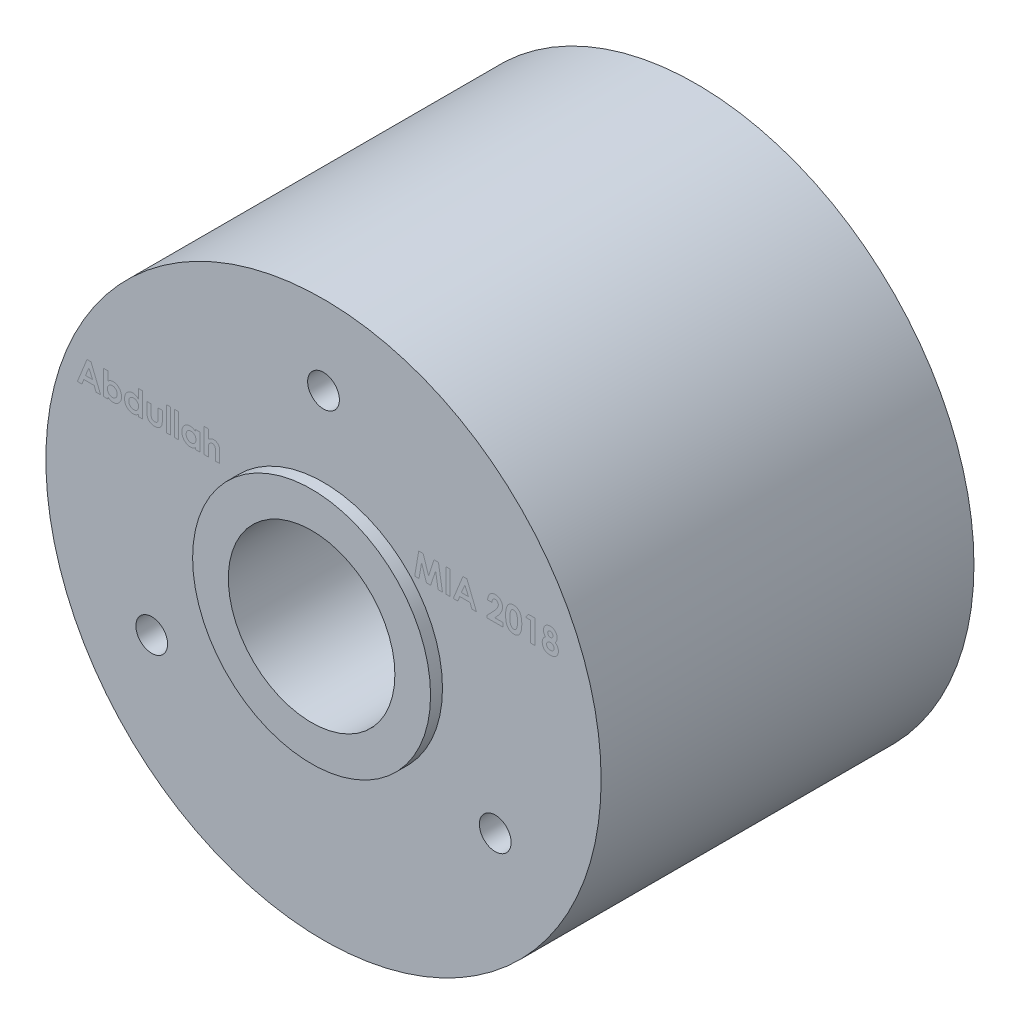
SolidWorks part; units mm, degrees
material "Nylon 101"
ref_plane "Front Plane" through (0, 0, 0) normal (0, 0, 1) x (1, 0, 0)
ref_plane "Top Plane" through (0, 0, 0) normal (0, 1, 0) x (1, 0, 0)
ref_plane "Right Plane" through (0, 0, 0) normal (1, 0, 0) x (0, 0, -1)
sketch "Sketch1" plane through (0, 0, 0) normal (0, 0, 1) x (1, 0, 0)
  circle A0 centre (0, 0) radius 35
  dimension "D1" = 70
extrude "Boss-Extrude1" add sketch "Sketch1" along normal mid plane 47
sketch "Sketch2" plane through (0, 0, 0) normal (0, 0, 1) x (1, 0, 0)
  circle A0 centre (0, 0) radius 15
  dimension "D1" = 30
extrude "Boss-Extrude2" add sketch "Sketch2" along normal mid plane 50
sketch "Sketch3" plane through (0, 0, 25) normal (0, 0, 1) x (1, 0, 0)
  circle A0 centre (0, 0) radius 10.5
  dimension "D1" = 21
extrude "Cut-Extrude1" cut sketch "Sketch3" against normal up to next
sketch "Sketch4" plane through (0, 0, 23.5) normal (0, 0, 1) x (1, 0, 0)
  circle A0 centre (0, 25) radius 2
  circle A1 centre (21.6506, -12.5) radius 2
  circle A2 centre (-21.6506, -12.5) radius 2
  point P10 (0, 0)
  dimension "D1" = 4
  dimension "D2" = 25
  dimension "D3" = 3
extrude "Cut-Extrude2" cut sketch "Sketch4" against normal up to next
sketch "Sketch6" plane through (0, 0, 23.5) normal (0, 0, 1) x (1, 0, 0)
  line L0 (33.3879, 10.5) -> (-33.3879, 10.5) construction
  circle A0 centre (0, 0) radius 35 construction
  text T0 "<b>  Abdullah                     MIA 2018</b>" font "Century Gothic" height 3
split line "Split Line7"
sketch "Sketch7" plane through (0, 0, -23.5) normal (0, 0, -1) x (-1, 0, 0)
  line L0 (-28.3324, -20.5493) -> (28.3324, -20.5493) construction
  circle A0 centre (0, 0) radius 35 construction
  text T0 "<b> bakty mal mn el-koer el-shmal</b>" font "Century Gothic" height in points 10
split line "Split Line8"
